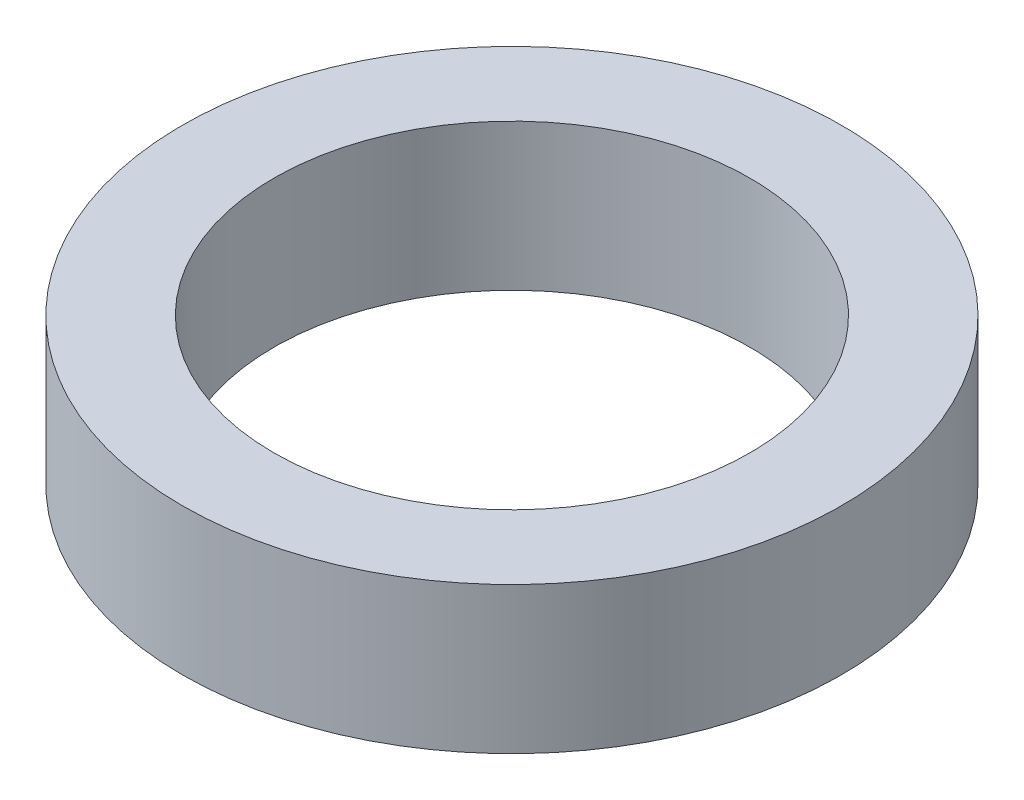
SolidWorks part; units mm, degrees
ref_plane "Front Plane" through (0, 0, 0) normal (0, 0, 1) x (1, 0, 0)
ref_plane "Top Plane" through (0, 0, 0) normal (0, 1, 0) x (1, 0, 0)
ref_plane "Right Plane" through (0, 0, 0) normal (1, 0, 0) x (0, 0, -1)
sketch "Sketch1" plane through (0, 0, 0) normal (0, 1, 0) x (1, 0, 0)
  circle A0 centre (0, 0) radius 6.5
  circle A1 centre (0, 0) radius 9
  dimension "D1" = 13
  dimension "D2" = 18
extrude "Boss-Extrude1" add sketch "Sketch1" along normal blind 4
